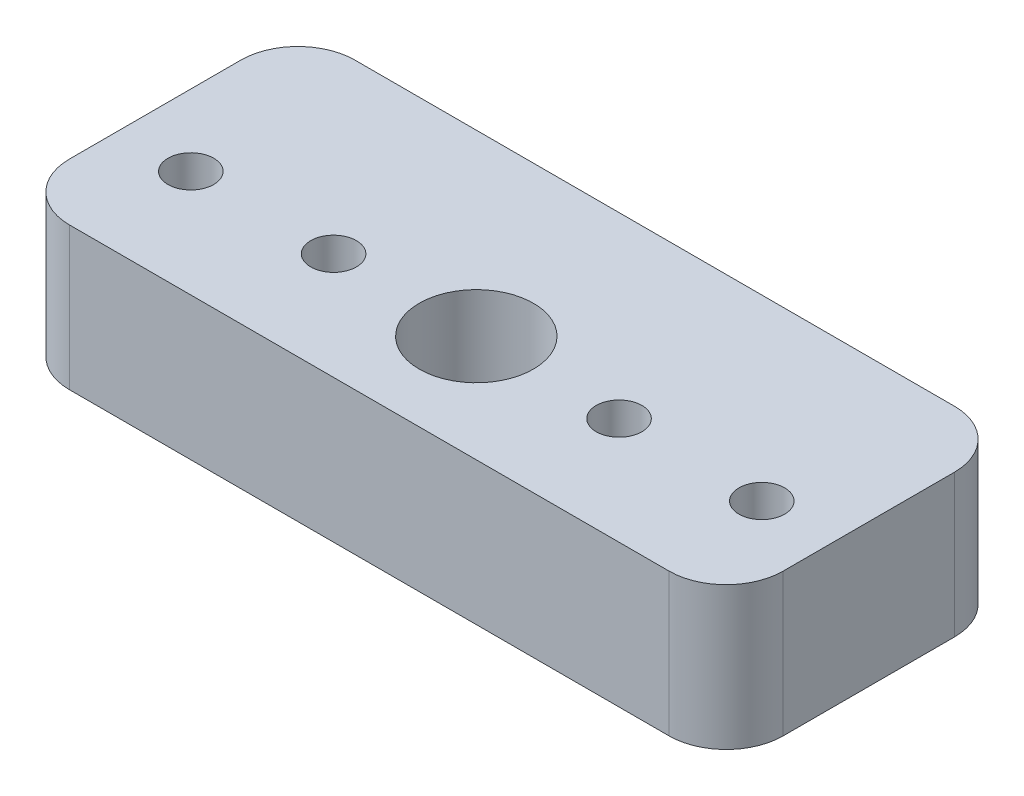
SolidWorks part; units mm, degrees
ref_plane "Front Plane" through (0, 0, 0) normal (0, 0, 1) x (1, 0, 0)
ref_plane "Top Plane" through (0, 0, 0) normal (0, 1, 0) x (1, 0, 0)
ref_plane "Right Plane" through (0, 0, 0) normal (1, 0, 0) x (0, 0, -1)
sketch "Sketch1" plane through (0, 0, 0) normal (0, 1, 0) x (1, 0, 0)
  line L0 (-25, -2.5) -> (25, -2.5) construction
  line L1 (-21, 10) -> (21, 10)
  line L2 (-25, 6) -> (-25, -6)
  line L3 (-21, -10) -> (21, -10)
  line L4 (25, 6) -> (25, -6)
  line L5 (-25, 10) -> (25, -10) construction
  line L6 (-25, -10) -> (25, 10) construction
  line L7 (0, -10) -> (0, 10) construction
  line L8 (25, 10) -> (-25, -10) construction
  arc A0 (-25, -6) -> (-21, -10) centre (-21, -6) ccw
  arc A1 (21, -10) -> (25, -6) centre (21, -6) ccw
  arc A2 (21, 10) -> (25, 6) centre (21, 6) cw
  arc A3 (-21, 10) -> (-25, 6) centre (-21, 6) ccw
  circle A4 centre (0, -2.5) radius 4
  circle A5 centre (10, -2.5) radius 1.6
  circle A6 centre (20, -2.5) radius 1.6
  circle A7 centre (-20, -2.5) radius 1.6
  circle A8 centre (-10, -2.5) radius 1.6
  point P0 (0, 0)
  dimension "D3" = 4
  dimension "D4" = 8
  dimension "D5" = 3.2
  dimension "D6" = 3.2
  dimension "D1" = 20
  dimension "D7" = 7.5
  dimension "D8" = 10
  dimension "D9" = 40
  dimension "D2" = 5
extrude "Boss-Extrude1" add sketch "Sketch1" along normal blind 10
equation "\"Y-ROD-SPACING\"=75"
equation "\"Y-BED-OFFSET\"=2"
equation "\"Y-BED-ROD-INSET\"=3.5"
equation "\"T-SLOT-NUT-FILLET-RADIUS\"=0.25"
equation "\"T-SLOT-SCREW-SHAFT-RADIUS\"=1.75"
equation "\"T-SLOT-SCREW-SHAFT-CUTOUT-LENGTH\"=10.5"
equation "\"T-SLOT-NUT-DEPTH\"=4.2"
equation "\"T-SLOT-NUT-WIDTH\"=3"
equation "\"T-SLOT-NUT-END-DISTANCE\"=8"
equation "\"ACRYLIC-TAB-CUTOUT-SIZE\"=\"ACRYLIC-THICKNESS\"+\"ACRYLIC-TAB-TOLERANCE\"*2"
equation "\"ACRYLIC-M3-HOLE\"=3.2"
equation "\"SMOOTHROD-CAP-SCREW-DISTANCE\"=20"
equation "\"D5@Sketch1\"=\"ACRYLIC-M3-HOLE\""
equation "\"D6@Sketch1\"=\"ACRYLIC-M3-HOLE\""
equation "\"D8@Sketch1\"=\"SMOOTHROD-CAP-SCREW-DISTANCE\"/2"
equation "\"ACRYLIC-TAB-WIDTH\"=\"ACRYLIC-THICKNESS\""
equation "\"FRAME-WIDTH-INNER\"=370"
equation "\"NEMA17-HOLE-SPACING\"=31"
equation "\"NEMA17-CENTRAL-CUTOUT\"=22.5"
equation "\"Z-BRACKET-REACH\"=55"
equation "\"TOP-BRACKET-SPACING\"=40"
equation "\"D9@Sketch1\"=\"TOP-BRACKET-SPACING\""
equation "\"D2@Sketch1\"=\"ACRYLIC-TAB-WIDTH\"/2"
equation "\"X-ROD-SPACING\"=45"
equation "\"Z-ROD-SPACING\"=17.5"
equation "\"ACRYLIC-THICKNESS\"=10"
equation "\"ACRYLIC-THICKNESS2\"=4.5"
equation "\"SMOOTHROD-X-LENGTH\"=350"
equation "\"SMOOTHROD-Y-LENGTH\"=350"
equation "\"SMOOTHROD-Z-LENGTH\"=350"
equation "\"SMOOTHROD-TIGHTENING-HEADROOM\"=1"
equation "\"LEADSCREW-Z-LENGTH\"=300"
equation "\"SCREW-LENGTH-FRAME\"=\"ACRYLIC-THICKNESS\" + 10"
equation "\"SCREW-HEAD-RADIUS\"=6"
equation "\"PRINTED-X-SMOOTHROD-DIAMETER\"=8.2"
equation "\"PRINTED-X-SMOOTHROD-CUTOUT\"=10"
equation "\"PRINTED-X-BASE-HEIGHT\"=10"
equation "\"PRINTED-LM8UU-CUTOUT-SIZE\"=16"
equation "\"PRINTED-LM8UU-CUTOUT-LENGTH\"=24.5"
equation "\"PRINTED-X-IDLER-HEIGHT\"=16"
equation "\"PSU-MOUNTING-WIDTH\"=95"
equation "\"PSU-MOUNTING-HEIGHT\"=177"
equation "\"D1@Boss-Extrude1\"=\"ACRYLIC-THICKNESS\""
